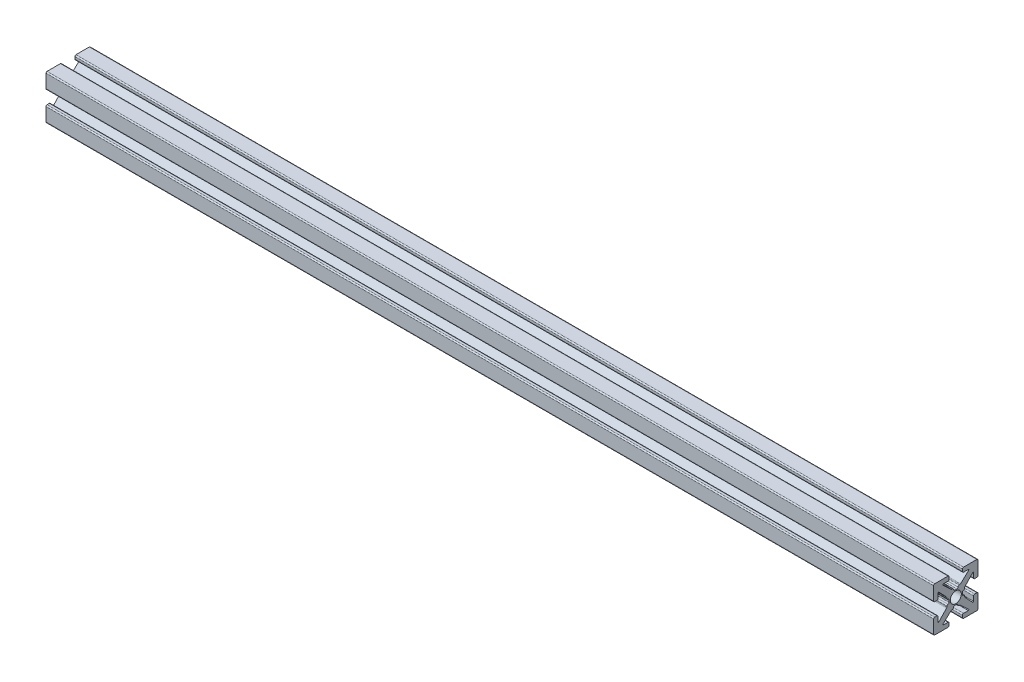
SolidWorks part; units mm, degrees
material "Acciaio in lega fuso"
ref_plane "Front Plane" through (0, 0, 0) normal (0, 0, 1) x (1, 0, 0)
ref_plane "Top Plane" through (0, 0, 0) normal (0, 1, 0) x (1, 0, 0)
ref_plane "Right Plane" through (0, 0, 0) normal (1, 0, 0) x (0, 0, -1)
sketch "Sketch1" plane through (0, 0, 0) normal (1, 0, 0) x (0, 0, -1)
  line L0 (0, 0) -> (0, 1.4986) construction
  line L1 (-0.2413, 1.4986) -> (0.2413, 1.4986)
  line L2 (5.0038, 1.7526) -> (5.0038, 4.7498)
  line L3 (0.7493, 2.0066) -> (0.8899, 2.0066)
  line L4 (1.0639, 2.0756) -> (2.8908, 3.7937)
  line L5 (2.8038, 4.0132) -> (1.7526, 4.0132)
  line L6 (1.4986, 4.2672) -> (1.4986, 4.7498)
  line L7 (1.7526, 5.0038) -> (4.7498, 5.0038)
  line L8 (5.0038, 5.0038) -> (0, 0) construction
  line L9 (0, 0) -> (8.6271, 0) construction
  line L10 (0, 0) -> (0, 5.0038) construction
  line L11 (4.2672, 1.4986) -> (4.7498, 1.4986)
  line L12 (4.0132, 2.8038) -> (4.0132, 1.7526)
  line L13 (2.0756, 1.0639) -> (3.7937, 2.8908)
  line L14 (2.0066, 0.7493) -> (2.0066, 0.8899)
  line L15 (1.4986, -0.2413) -> (1.4986, 0.2413)
  line L16 (0, 0) -> (1.4986, 0) construction
  line L17 (-0.2413, -1.4986) -> (0.2413, -1.4986)
  line L18 (0.7493, -2.0066) -> (0.8899, -2.0066)
  line L19 (1.0639, -2.0756) -> (2.8908, -3.7937)
  line L20 (2.8038, -4.0132) -> (1.7526, -4.0132)
  line L21 (1.4986, -4.2672) -> (1.4986, -4.7498)
  line L22 (1.7526, -5.0038) -> (4.7498, -5.0038)
  line L23 (5.0038, -1.7526) -> (5.0038, -4.7498)
  line L24 (4.2672, -1.4986) -> (4.7498, -1.4986)
  line L25 (4.0132, -2.8038) -> (4.0132, -1.7526)
  line L26 (2.0756, -1.0639) -> (3.7937, -2.8908)
  line L27 (2.0066, -0.7493) -> (2.0066, -0.8899)
  line L28 (-0.7493, 2.0066) -> (-0.8899, 2.0066)
  line L29 (-1.0639, 2.0756) -> (-2.8908, 3.7937)
  line L30 (-2.8038, 4.0132) -> (-1.7526, 4.0132)
  line L31 (-1.4986, 4.2672) -> (-1.4986, 4.7498)
  line L32 (-1.7526, 5.0038) -> (-4.7498, 5.0038)
  line L33 (-5.0038, 1.7526) -> (-5.0038, 4.7498)
  line L34 (-4.2672, 1.4986) -> (-4.7498, 1.4986)
  line L35 (-4.0132, 2.8038) -> (-4.0132, 1.7526)
  line L36 (-2.0756, 1.0639) -> (-3.7937, 2.8908)
  line L37 (-2.0066, 0.7493) -> (-2.0066, 0.8899)
  line L38 (-1.4986, -0.2413) -> (-1.4986, 0.2413)
  line L39 (-2.0066, -0.7493) -> (-2.0066, -0.8899)
  line L40 (-2.0756, -1.0639) -> (-3.7937, -2.8908)
  line L41 (-4.0132, -2.8038) -> (-4.0132, -1.7526)
  line L42 (-4.2672, -1.4986) -> (-4.7498, -1.4986)
  line L43 (-5.0038, -1.7526) -> (-5.0038, -4.7498)
  line L44 (-1.7526, -5.0038) -> (-4.7498, -5.0038)
  line L45 (-1.4986, -4.2672) -> (-1.4986, -4.7498)
  line L46 (-2.8038, -4.0132) -> (-1.7526, -4.0132)
  line L47 (-1.0639, -2.0756) -> (-2.8908, -3.7937)
  line L48 (-0.7493, -2.0066) -> (-0.8899, -2.0066)
  arc A0 (2.8908, 3.7937) -> (2.8038, 4.0132) centre (2.8038, 3.8862) ccw
  arc A1 (0.4953, 1.7526) -> (0.7493, 2.0066) centre (0.7493, 1.7526) cw
  arc A2 (0.8899, 2.0066) -> (1.0639, 2.0756) centre (0.8899, 2.2606) ccw
  arc A3 (1.7526, 4.0132) -> (1.4986, 4.2672) centre (1.7526, 4.2672) cw
  arc A4 (1.4986, 4.7498) -> (1.7526, 5.0038) centre (1.7526, 4.7498) cw
  arc A5 (0.2413, 1.4986) -> (0.4953, 1.7526) centre (0.2413, 1.7526) ccw
  arc A6 (4.7498, 1.4986) -> (5.0038, 1.7526) centre (4.7498, 1.7526) ccw
  arc A7 (4.0132, 1.7526) -> (4.2672, 1.4986) centre (4.2672, 1.7526) ccw
  arc A8 (3.7937, 2.8908) -> (4.0132, 2.8038) centre (3.8862, 2.8038) cw
  arc A9 (2.0066, 0.8899) -> (2.0756, 1.0639) centre (2.2606, 0.8899) cw
  arc A10 (1.7526, 0.4953) -> (2.0066, 0.7493) centre (1.7526, 0.7493) ccw
  arc A11 (1.4986, 0.2413) -> (1.7526, 0.4953) centre (1.7526, 0.2413) cw
  arc A12 (0.2413, -1.4986) -> (0.4953, -1.7526) centre (0.2413, -1.7526) cw
  arc A13 (0.4953, -1.7526) -> (0.7493, -2.0066) centre (0.7493, -1.7526) ccw
  arc A14 (0.8899, -2.0066) -> (1.0639, -2.0756) centre (0.8899, -2.2606) cw
  arc A15 (2.8908, -3.7937) -> (2.8038, -4.0132) centre (2.8038, -3.8862) cw
  arc A16 (1.7526, -4.0132) -> (1.4986, -4.2672) centre (1.7526, -4.2672) ccw
  arc A17 (1.4986, -4.7498) -> (1.7526, -5.0038) centre (1.7526, -4.7498) ccw
  arc A18 (4.7498, -1.4986) -> (5.0038, -1.7526) centre (4.7498, -1.7526) cw
  arc A19 (4.0132, -1.7526) -> (4.2672, -1.4986) centre (4.2672, -1.7526) cw
  arc A20 (3.7937, -2.8908) -> (4.0132, -2.8038) centre (3.8862, -2.8038) ccw
  arc A21 (2.0066, -0.8899) -> (2.0756, -1.0639) centre (2.2606, -0.8899) ccw
  arc A22 (1.7526, -0.4953) -> (2.0066, -0.7493) centre (1.7526, -0.7493) cw
  arc A23 (1.4986, -0.2413) -> (1.7526, -0.4953) centre (1.7526, -0.2413) ccw
  arc A24 (-0.2413, 1.4986) -> (-0.4953, 1.7526) centre (-0.2413, 1.7526) cw
  arc A25 (-0.4953, 1.7526) -> (-0.7493, 2.0066) centre (-0.7493, 1.7526) ccw
  arc A26 (-0.8899, 2.0066) -> (-1.0639, 2.0756) centre (-0.8899, 2.2606) cw
  arc A27 (-2.8908, 3.7937) -> (-2.8038, 4.0132) centre (-2.8038, 3.8862) cw
  arc A28 (-1.7526, 4.0132) -> (-1.4986, 4.2672) centre (-1.7526, 4.2672) ccw
  arc A29 (-1.4986, 4.7498) -> (-1.7526, 5.0038) centre (-1.7526, 4.7498) ccw
  arc A30 (-4.7498, 1.4986) -> (-5.0038, 1.7526) centre (-4.7498, 1.7526) cw
  arc A31 (-4.0132, 1.7526) -> (-4.2672, 1.4986) centre (-4.2672, 1.7526) cw
  arc A32 (-3.7937, 2.8908) -> (-4.0132, 2.8038) centre (-3.8862, 2.8038) ccw
  arc A33 (-2.0066, 0.8899) -> (-2.0756, 1.0639) centre (-2.2606, 0.8899) ccw
  arc A34 (-1.7526, 0.4953) -> (-2.0066, 0.7493) centre (-1.7526, 0.7493) cw
  arc A35 (-1.4986, 0.2413) -> (-1.7526, 0.4953) centre (-1.7526, 0.2413) ccw
  arc A36 (-1.4986, -0.2413) -> (-1.7526, -0.4953) centre (-1.7526, -0.2413) cw
  arc A37 (-1.7526, -0.4953) -> (-2.0066, -0.7493) centre (-1.7526, -0.7493) ccw
  arc A38 (-2.0066, -0.8899) -> (-2.0756, -1.0639) centre (-2.2606, -0.8899) cw
  arc A39 (-3.7937, -2.8908) -> (-4.0132, -2.8038) centre (-3.8862, -2.8038) cw
  arc A40 (-4.0132, -1.7526) -> (-4.2672, -1.4986) centre (-4.2672, -1.7526) ccw
  arc A41 (-4.7498, -1.4986) -> (-5.0038, -1.7526) centre (-4.7498, -1.7526) ccw
  arc A42 (-1.4986, -4.7498) -> (-1.7526, -5.0038) centre (-1.7526, -4.7498) cw
  arc A43 (-1.7526, -4.0132) -> (-1.4986, -4.2672) centre (-1.7526, -4.2672) cw
  arc A44 (-2.8908, -3.7937) -> (-2.8038, -4.0132) centre (-2.8038, -3.8862) ccw
  arc A45 (-0.8899, -2.0066) -> (-1.0639, -2.0756) centre (-0.8899, -2.2606) ccw
  arc A46 (-0.4953, -1.7526) -> (-0.7493, -2.0066) centre (-0.7493, -1.7526) cw
  arc A47 (-0.2413, -1.4986) -> (-0.4953, -1.7526) centre (-0.2413, -1.7526) ccw
  arc A48 (-4.7498, 5.0038) -> (-5.0038, 4.7498) centre (-4.7498, 4.7498) ccw
  arc A49 (-5.0038, -4.7498) -> (-4.7498, -5.0038) centre (-4.7498, -4.7498) ccw
  arc A50 (4.7498, -5.0038) -> (5.0038, -4.7498) centre (4.7498, -4.7498) ccw
  arc A51 (4.7498, 5.0038) -> (5.0038, 4.7498) centre (4.7498, 4.7498) cw
  point P14 (3.1242, 4.0132)
  point P19 (0.9906, 2.0066)
  point P150 (0, -1.4986)
  point P152 (-5.0038, 5.0038)
  point P155 (-5.0038, -5.0038)
  point P158 (5.0038, -5.0038)
  dimension "D10" = 0.127
  dimension "D11" = 0.254
  dimension "D2" = 0.254
  dimension "D1" = 10.0076
  dimension "D3" = 2.9972
  dimension "D4" = 0.508
  dimension "D5" = 2.9972
  dimension "D6" = 0.9906
  dimension "D7" = 1.6256
  dimension "D8" = 1.9812
  dimension "D9" = 0.9906
extrude "Estrusione-Estrusione1" add sketch "Sketch1" along normal blind 200 contours L36 A32 L35 A31 L34 A30 L33 A48 L32 A29 L31 A28 L30 A27 L29 A26 L28 A25 A24 L1 A5 A1 L3 A2 L4 A0 L5 A3 L6 A4 L7 A51 L2 A6 L11 A7 L12 A8 L13 A9 L14 A10 A11 L15 A23 A22 L27 A21 L26 A20 L25 A19 L24 A18 L23 A50 L22 A17 L21 A16 L20 A15 L19 A14 L18 A13 A12 L17 A47 A46 L48 A45 L47 A44 L46 A43 L45 A42 L44 A49 L43 A41 L42 A40 L41 A39 L40 A38 L39 A37 A36 L38 A35 A34 L37 A33
hole_wizard "Foro filettato M3x0.5-1" positions "Schizzo2" profile "Schizzo1" tap size "M3x0.5" standard "Ansi Metric" end condition through all
sketch "Schizzo2" plane through (0, 0, 0) normal (-1, 0, 0) x (0, 0, 1)
  point P0 (0, 0)
sketch "Schizzo1" plane through (0, 0, 0) normal (0, 1, 0) x (0, 0, 1)
  line L0 (0, 0) -> (0, 200)
  line L1 (0, 200) -> (1.25, 200)
  line L2 (1.25, 200) -> (1.25, 0)
  line L5 (1.25, 0) -> (0, 0)
  line L11 (0, -6.35) -> (0, 107.95) construction
  dimension "Thread Major Dia." = 2.5
  dimension "Thru Tap Drill Depth" = 200
